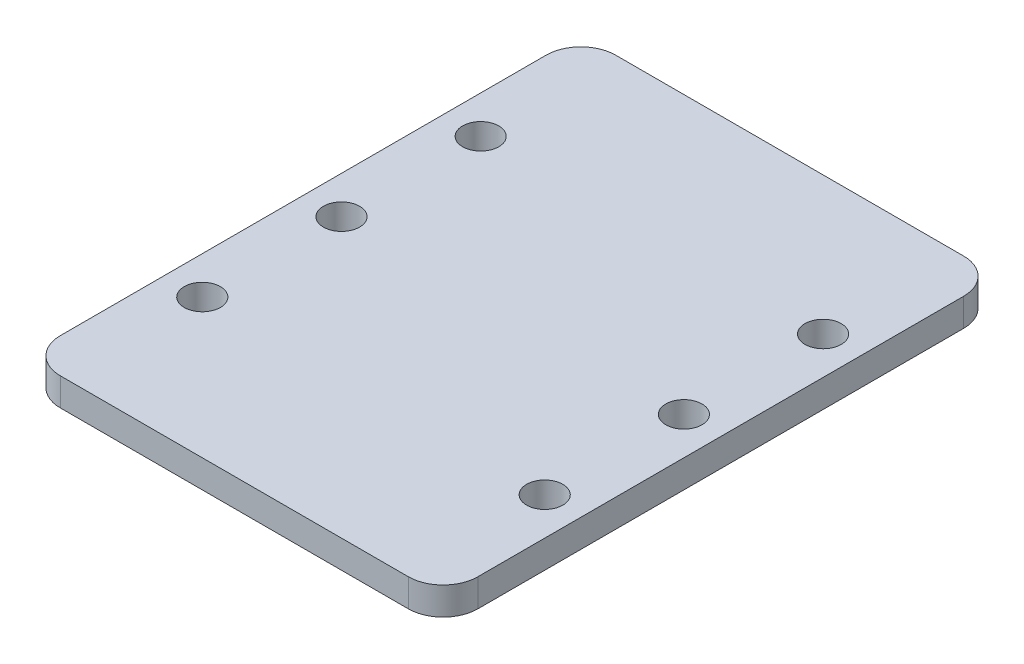
SolidWorks part; units mm, degrees
material "Acrylic (Medium-high impact)"
ref_plane "Front Plane" through (0, 0, 0) normal (0, 0, 1) x (1, 0, 0)
ref_plane "Top Plane" through (0, 0, 0) normal (0, 1, 0) x (1, 0, 0)
ref_plane "Right Plane" through (0, 0, 0) normal (1, 0, 0) x (0, 0, -1)
sketch "Sketch1" plane through (0, 0, 0) normal (0, 1, 0) x (1, 0, 0)
  line L0 (-146.05, -95.25) -> (-44.45, -95.25) construction
  line L2 (-177.8, -152.4) -> (-177.8, -139.7) construction
  line L3 (-177.8, 152.4) -> (-165.1, 152.4) construction
  line L4 (177.8, -152.4) -> (177.8, -139.7) construction
  line L5 (-177.8, -152.4) -> (177.8, 152.4) construction
  line L6 (-177.8, 152.4) -> (177.8, -152.4) construction
  line L7 (-95.25, -95.25) -> (95.25, -95.25) construction
  line L8 (-95.25, -95.25) -> (-95.25, 95.25) construction
  line L9 (-95.25, 95.25) -> (95.25, 95.25) construction
  line L10 (95.25, -95.25) -> (95.25, 95.25) construction
  line L11 (-95.25, -95.25) -> (95.25, 95.25) construction
  line L12 (-95.25, 95.25) -> (95.25, -95.25) construction
  line L13 (44.45, -95.25) -> (146.05, -95.25) construction
  line L14 (-95.25, -95.25) -> (-95.25, -0.2308) construction
  line L15 (95.25, -95.25) -> (95.25, -90.3446) construction
  line L16 (-177.8, 0) -> (170.1699, 0) construction
  line L17 (44.45, 95.25) -> (146.05, 95.25) construction
  line L18 (95.25, 95.25) -> (95.25, 90.3446) construction
  line L19 (-95.25, 95.25) -> (-95.25, -0.2308) construction
  line L20 (-146.05, 95.25) -> (-44.45, 95.25) construction
  line L21 (-177.8, -152.4) -> (-165.1, -152.4) construction
  line L22 (-146.05, 95.25) -> (-44.45, 95.25) construction
  line L23 (-146.05, 95.25) -> (-146.05, 142.24) construction
  line L24 (-146.05, 142.24) -> (-44.45, 142.24) construction
  line L25 (-44.45, 95.25) -> (-44.45, 142.24) construction
  line L26 (44.45, 95.25) -> (146.05, 95.25) construction
  line L27 (44.45, 95.25) -> (44.45, 142.24) construction
  line L28 (44.45, 142.24) -> (146.05, 142.24) construction
  line L29 (146.05, 95.25) -> (146.05, 142.24) construction
  line L30 (-110.871, 87.376) -> (-110.871, 38.1) construction
  line L31 (-146.05, -95.25) -> (-44.45, -95.25) construction
  line L33 (-146.05, -142.24) -> (-44.45, -142.24) construction
  line L34 (-44.45, -95.25) -> (-44.45, -142.24) construction
  line L35 (44.45, -95.25) -> (146.05, -95.25) construction
  line L36 (44.45, -95.25) -> (44.45, -142.24) construction
  line L37 (44.45, -142.24) -> (146.05, -142.24) construction
  line L39 (-114.046, 87.376) -> (-76.454, 87.376) construction
  line L40 (-114.046, 87.376) -> (-114.046, 38.1) construction
  line L41 (-114.046, 38.1) -> (-76.454, 38.1) construction
  line L42 (-76.454, 87.376) -> (-76.454, 38.1) construction
  line L43 (-79.629, 38.1) -> (-79.629, 87.376) construction
  line L44 (0, 148.6976) -> (0, -148.6976) construction
  line L45 (-177.8, 139.7) -> (-177.8, 152.4) construction
  line L46 (177.8, 139.7) -> (177.8, 152.4) construction
  line L49 (165.1, -152.4) -> (177.8, -152.4) construction
  line L50 (165.1, 152.4) -> (177.8, 152.4) construction
  line L51 (146.05, -95.25) -> (173.7468, -95.25) construction
  line L52 (44.45, -26.67) -> (146.05, -26.67) construction
  line L53 (44.45, -26.67) -> (44.45, 26.67) construction
  line L54 (44.45, 26.67) -> (146.05, 26.67) construction
  line L55 (146.05, -26.67) -> (146.05, 26.67) construction
  line L56 (44.45, -26.67) -> (146.05, 26.67) construction
  line L57 (44.45, 26.67) -> (146.05, -26.67) construction
  line L58 (-31.75, -142.24) -> (31.75, -142.24) construction
  line L62 (-31.75, -87.63) -> (31.75, -87.63) construction
  line L64 (44.45, -142.24) -> (-44.45, -142.24) construction
  line L65 (-146.05, -95.25) -> (-173.7468, -95.25) construction
  line L66 (-146.05, 95.25) -> (-173.7468, 95.25) construction
  line L67 (146.05, 95.25) -> (173.7468, 95.25) construction
  line L68 (-44.45, 142.24) -> (44.45, 142.24) construction
  line L69 (-31.75, -134.62) -> (31.75, -134.62) construction
  line L70 (-31.75, -134.62) -> (-31.75, -40.64) construction
  line L71 (-31.75, -40.64) -> (31.75, -40.64) construction
  line L72 (31.75, -134.62) -> (31.75, -40.64) construction
  line L73 (-114.046, 62.738) -> (-114.3, 62.738) construction
  line L74 (-76.2, 43.053) -> (-114.3, 43.053)
  line L76 (-76.2, 93.726) -> (-114.3, 93.726)
  line L77 (-114.3, 43.053) -> (-114.3, 93.726)
  line L78 (-76.454, 62.738) -> (-76.2, 62.738) construction
  line L79 (-98.9513, 87.376) -> (-98.9513, 93.726) construction
  line L81 (-76.2, 93.726) -> (-76.2, 43.053)
  circle A0 centre (-110.871, 81.153) radius 1.651
  circle A1 centre (-110.871, 74.803) radius 1.651 construction
  circle A2 centre (-110.871, 68.453) radius 1.651
  circle A3 centre (-110.871, 62.103) radius 1.651 construction
  circle A4 centre (-110.871, 55.753) radius 1.651
  circle A5 centre (-110.871, 49.403) radius 1.651 construction
  circle A6 centre (-110.871, 43.053) radius 1.651 construction
  circle A7 centre (-79.629, 81.153) radius 1.651
  circle A8 centre (-79.629, 74.803) radius 1.651 construction
  circle A9 centre (-79.629, 68.453) radius 1.651
  circle A10 centre (-79.629, 62.103) radius 1.651 construction
  circle A11 centre (-79.629, 55.753) radius 1.651
  circle A12 centre (-79.629, 43.053) radius 1.651 construction
  circle A13 centre (-79.629, 49.403) radius 1.651 construction
  circle A14 centre (79.629, 43.053) radius 1.651 construction
  circle A15 centre (110.871, 43.053) radius 1.651 construction
  circle A16 centre (110.871, 49.403) radius 1.651 construction
  circle A17 centre (79.629, 49.403) radius 1.651 construction
  circle A18 centre (79.629, 55.753) radius 1.651 construction
  circle A19 centre (110.871, 55.753) radius 1.651 construction
  circle A20 centre (110.871, 62.103) radius 1.651 construction
  circle A21 centre (79.629, 62.103) radius 1.651 construction
  circle A22 centre (79.629, 68.453) radius 1.651 construction
  circle A23 centre (110.871, 68.453) radius 1.651 construction
  circle A24 centre (110.871, 74.803) radius 1.651 construction
  circle A25 centre (79.629, 74.803) radius 1.651 construction
  circle A26 centre (79.629, 81.153) radius 1.651 construction
  circle A27 centre (110.871, 81.153) radius 1.651 construction
  circle A28 centre (79.629, -43.053) radius 1.651 construction
  circle A29 centre (110.871, -43.053) radius 1.651 construction
  circle A30 centre (110.871, -49.403) radius 1.651 construction
  circle A31 centre (79.629, -49.403) radius 1.651 construction
  circle A32 centre (79.629, -55.753) radius 1.651 construction
  circle A33 centre (110.871, -55.753) radius 1.651 construction
  circle A34 centre (110.871, -62.103) radius 1.651 construction
  circle A35 centre (79.629, -62.103) radius 1.651 construction
  circle A36 centre (110.871, -68.453) radius 1.651 construction
  circle A37 centre (79.629, -68.453) radius 1.651 construction
  circle A38 centre (79.629, -74.803) radius 1.651 construction
  circle A39 centre (110.871, -74.803) radius 1.651 construction
  circle A40 centre (110.871, -81.153) radius 1.651 construction
  circle A41 centre (79.629, -81.153) radius 1.651 construction
  circle A42 centre (-79.629, -43.053) radius 1.651 construction
  circle A43 centre (-110.871, -43.053) radius 1.651 construction
  circle A44 centre (-110.871, -49.403) radius 1.651 construction
  circle A45 centre (-79.629, -49.403) radius 1.651 construction
  circle A46 centre (-79.629, -55.753) radius 1.651 construction
  circle A47 centre (-110.871, -55.753) radius 1.651 construction
  circle A48 centre (-110.871, -62.103) radius 1.651 construction
  circle A49 centre (-79.629, -62.103) radius 1.651 construction
  circle A50 centre (-79.629, -68.453) radius 1.651 construction
  circle A51 centre (-110.871, -68.453) radius 1.651 construction
  circle A52 centre (-110.871, -74.803) radius 1.651 construction
  circle A53 centre (-79.629, -74.803) radius 1.651 construction
  circle A54 centre (-79.629, -81.153) radius 1.651 construction
  circle A55 centre (-110.871, -81.153) radius 1.651 construction
  arc A56 (-163.9664, 152.3493) -> (-177.7245, 138.3168) centre (-165.1, 139.7) ccw construction
  arc A57 (-163.9664, -152.3493) -> (-177.7245, -138.3168) centre (-165.1, -139.7) cw construction
  arc A58 (-177.7245, 138.3168) -> (-177.7245, -138.3168) centre (-1440.1699, 0) cw construction
  arc A59 (163.9664, -152.3493) -> (177.7245, -138.3168) centre (165.1, -139.7) ccw construction
  arc A60 (177.7245, 138.3168) -> (177.7245, -138.3168) centre (1440.1699, 0) ccw construction
  arc A61 (163.9664, 152.3493) -> (177.7245, 138.3168) centre (165.1, 139.7) cw construction
  arc A62 (-165.1, 152.4) -> (165.1, 152.4) centre (0, 3831.6976) ccw construction
  circle A64 centre (-165.1, 139.7) radius 1.8415 construction
  circle A65 centre (-165.1, -139.7) radius 1.8415 construction
  circle A66 centre (165.1, -139.7) radius 1.8415 construction
  circle A67 centre (165.1, 139.7) radius 1.8415 construction
  circle A68 centre (59.69, 24.13) radius 1.5875 construction
  circle A69 centre (58.42, -24.13) radius 1.5875 construction
  circle A70 centre (141.4145, -24.13) radius 1.5875 construction
  circle A71 centre (134.62, 24.13) radius 1.5875 construction
  circle A72 centre (110.49, 8.89) radius 1.5875 construction
  circle A73 centre (110.49, -19.05) radius 1.5875 construction
  circle A82 centre (165.1, 96.52) radius 1.8415 construction
  circle A84 centre (165.1, -96.52) radius 1.8415 construction
  circle A86 centre (158.75, 0) radius 1.8415 construction
  arc A88 (-173.7468, -95.25) -> (-173.7468, 95.25) centre (-1440.1699, 0) ccw construction
  arc A89 (173.7468, 95.25) -> (173.7468, -95.25) centre (1440.1699, 0) ccw construction
  circle A90 centre (-27.94, -130.81) radius 1.905 construction
  circle A91 centre (27.94, -130.81) radius 1.905 construction
  circle A92 centre (-27.94, -44.45) radius 1.905 construction
  circle A93 centre (27.94, -44.45) radius 1.905 construction
  circle A94 centre (27.94, 44.45) radius 1.905 construction
  circle A95 centre (-27.94, 44.45) radius 1.905 construction
  circle A96 centre (-27.94, 130.81) radius 1.905 construction
  circle A97 centre (27.94, 130.81) radius 1.905 construction
  circle A98 centre (0, 0) radius 1.8415 construction
  circle A99 centre (-161.0468, 82.55) radius 1.8415 construction
  circle A100 centre (-161.0468, -82.55) radius 1.8415 construction
  circle A101 centre (161.0468, -82.55) radius 1.8415 construction
  circle A102 centre (161.0468, 82.55) radius 1.8415 construction
  circle A103 centre (-53.34, 0) radius 1.8415 construction
  circle A104 centre (-106.68, 0) radius 1.8415 construction
  circle A105 centre (-160.02, 0) radius 1.8415 construction
  point P0 (0, 0)
  point P6 (0, 0)
  point P37 (-95.25, 87.376)
  point P188 (95.25, 0)
  point P205 (0, -95.25)
  dimension "D17" = 3.302
  dimension "D19" = 4.953
  dimension "D21" = 25.4
  dimension "D22" = 1270
  dimension "D23" = 3683
  dimension "D24" = 3.683
  dimension "D25" = 3.683
  dimension "D26" = 3.683
  dimension "D27" = 3.683
  dimension "D31" = 3.175
  dimension "D42" = 93.98
  dimension "D48" = 3.683
  dimension "D50" = 3.683
  dimension "D51" = 3.81
  dimension "D52" = 3.81
  dimension "D57" = 3.683
  dimension "D60" = 4
  dimension "D1" = 355.6
  dimension "D2" = 304.8
  dimension "D3" = 101.6
  dimension "D4" = 101.6
  dimension "D5" = 190.5
  dimension "D6" = 190.5
  dimension "D7" = 190.5
  dimension "D8" = 46.99
  dimension "D9" = 46.99
  dimension "D10" = 46.99
  dimension "D11" = 46.99
  dimension "D12" = 7.874
  dimension "D13" = 49.276
  dimension "D14" = 37.592
  dimension "D15" = 31.242
  dimension "D16" = 15.621
  dimension "D20" = 6.35
  dimension "D28" = 101.6
  dimension "D29" = 53.34
  dimension "D30" = 15.24
  dimension "D32" = 13.97
  dimension "D33" = 2.54
  dimension "D34" = 5.08
  dimension "D35" = 27.94
  dimension "D36" = 50.8
  dimension "D37" = 15.24
  dimension "D38" = 24.13
  dimension "D39" = 4.6355
  dimension "D40" = 63.5
  dimension "D41" = 31.75
  dimension "D43" = 7.62
  dimension "D44" = 46.99
  dimension "D45" = 19.05
  dimension "D46" = 45.72
  dimension "D47" = 19.05
  dimension "D49" = 12.7
  dimension "D53" = 3.81
  dimension "D54" = 3.81
  dimension "D55" = 3.81
  dimension "D56" = 3.81
  dimension "D58" = 12.7
  dimension "D59" = 12.7
  dimension "D61" = 53.34
  dimension "D62" = 38.1
  dimension "D63" = 6.35
  dimension "D18" = 7
extrude "Boss-Extrude1" add sketch "Sketch1" along normal blind 2.54
fillet "Fillet1" radius 3.175 4 edges at (-114.3, 1.27, -43.053) (-114.3, 1.27, -93.726) (-76.2, 1.27, -43.053) (-76.2, 1.27, -93.726)
